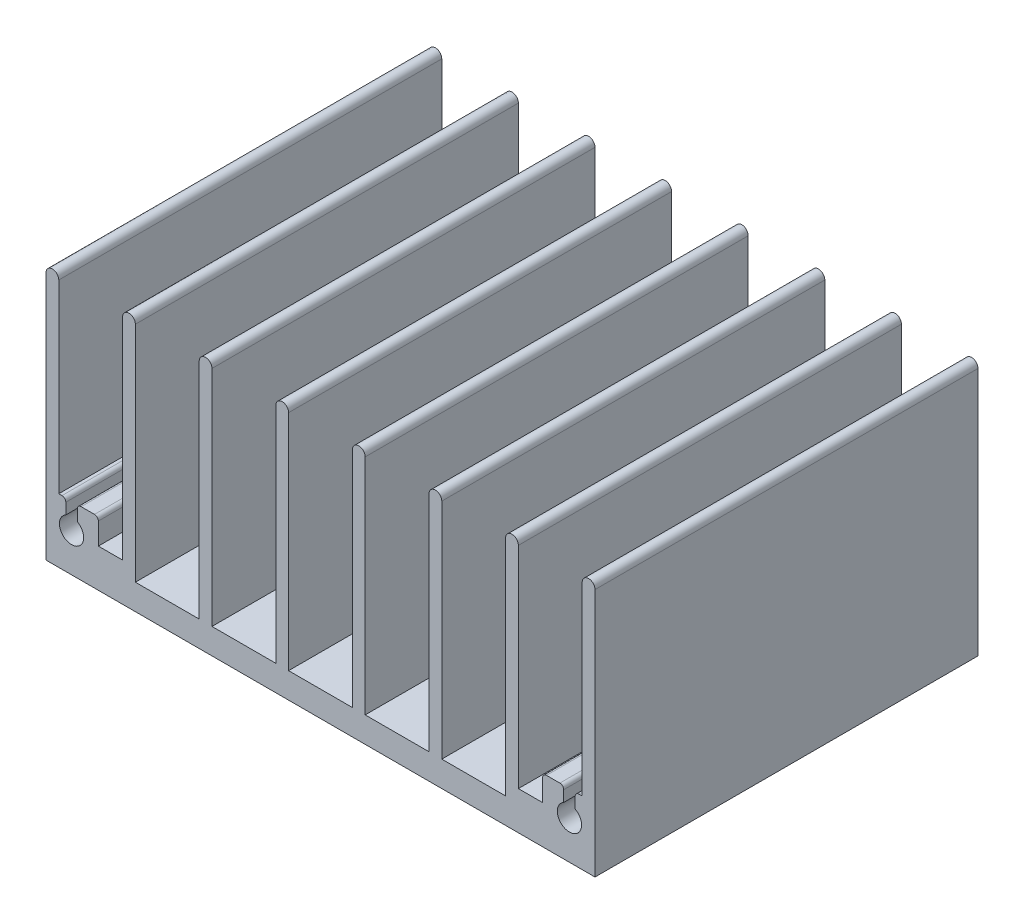
SolidWorks part; units mm, degrees
ref_plane "Front" through (0, 0, 0) normal (0, 0, 1) x (1, 0, 0)
ref_plane "Top" through (0, 0, 0) normal (0, 1, 0) x (1, 0, 0)
ref_plane "Right" through (0, 0, 0) normal (1, 0, 0) x (0, 0, -1)
sketch "Эскиз1" plane through (0, 0, 0) normal (0, 0, 1) x (1, 0, 0)
  line L10 (21.5, 0) -> (-21.5, 0)
  line L18 (21.5, 0) -> (21.5, 19.5)
  line L19 (20.5, 19.5) -> (20.5, 5)
  line L22 (24.9247, 20) -> (-25.9424, 20) construction
  line L23 (19.5, 3) -> (-19.5, 3) construction
  line L24 (0, 3) -> (0, 0) construction
  line L25 (19.05, 3.8367) -> (19.05, 5)
  line L26 (19.05, 5) -> (17.4, 5)
  line L27 (17.4, 5) -> (17.4, 3)
  line L28 (17.4, 3) -> (15.5, 3)
  line L29 (15.5, 3) -> (15.5, 19.5)
  line L30 (19.95, 3.8367) -> (19.95, 5)
  line L31 (19.95, 5) -> (20.5, 5)
  line L32 (14.5, 19.5) -> (14.5, 2)
  line L33 (14.5, 2) -> (9.5, 2)
  line L34 (9.5, 2) -> (9.5, 19.5)
  line L35 (8.5, 19.5) -> (8.5, 2)
  line L36 (8.5, 2) -> (3.5, 2)
  line L37 (3.5, 2) -> (3.5, 19.5)
  line L38 (2.5, 19.5) -> (2.5, 2)
  line L40 (-2.5, 2) -> (-2.5, 19.5)
  line L41 (-3.5, 19.5) -> (-3.5, 2)
  line L42 (-3.5, 2) -> (-8.5, 2)
  line L43 (-8.5, 2) -> (-8.5, 19.5)
  line L44 (-9.5, 19.5) -> (-9.5, 2)
  line L45 (-21.5, 0) -> (-21.5, 19.5)
  line L46 (-20.5, 19.5) -> (-20.5, 5)
  line L47 (-20.5, 5) -> (-19.95, 5)
  line L48 (-19.95, 5) -> (-19.95, 3.8367)
  line L49 (2.5, 2) -> (-2.5, 2)
  line L51 (-19.05, 3.8367) -> (-19.05, 5)
  line L52 (-19.05, 5) -> (-17.4, 5)
  line L53 (-17.4, 5) -> (-17.4, 3)
  line L54 (-17.4, 3) -> (-15.5, 3)
  line L55 (19.95, 5) -> (19.05, 5) construction
  line L56 (-19.95, 5) -> (-19.05, 5) construction
  line L57 (-15.5, 3) -> (-15.5, 19.5)
  line L58 (-14.5, 19.5) -> (-14.5, 2)
  line L59 (-14.5, 2) -> (-9.5, 2)
  line L60 (-20.5, 5) -> (-15.5, 5) construction
  line L61 (20.5, 5) -> (15.5, 5) construction
  arc A12 (21.5, 19.5) -> (20.5, 19.5) centre (21, 19.5) ccw
  arc A15 (19.05, 3.8367) -> (19.95, 3.8367) centre (19.5, 3) ccw
  arc A16 (-19.95, 3.8367) -> (-19.05, 3.8367) centre (-19.5, 3) ccw
  arc A17 (15.5, 19.5) -> (14.5, 19.5) centre (15, 19.5) ccw
  arc A18 (9.5, 19.5) -> (8.5, 19.5) centre (9, 19.5) ccw
  arc A19 (3.5, 19.5) -> (2.5, 19.5) centre (3, 19.5) ccw
  arc A20 (-2.5, 19.5) -> (-3.5, 19.5) centre (-3, 19.5) ccw
  arc A21 (-8.5, 19.5) -> (-9.5, 19.5) centre (-9, 19.5) ccw
  arc A22 (-21.5, 19.5) -> (-20.5, 19.5) centre (-21, 19.5) cw
  arc A23 (-15.5, 19.5) -> (-14.5, 19.5) centre (-15, 19.5) cw
  point P2 (0, 0)
  point P36 (-3.4686, 0.7542)
  point P37 (2.3591, 1.0573)
  point P53 (0, 2)
  point P64 (-2.4432, 1.1245)
  point P65 (0, 0)
  dimension "D1" = 43
  dimension "D6" = 0.95
  dimension "D10" = 5
  dimension "D11" = 2
  dimension "D2" = 1
  dimension "D4" = 39
  dimension "D9" = 1.9
  dimension "D3" = 20
  dimension "D5" = 3
  dimension "D7" = 5
  dimension "D8" = 0.9
extrude "Бобышка-Вытянуть1" add sketch "Эскиз1" along normal blind 30
fillet "Скругление1" radius 0.3 6 edges at (17.4, 5, 15) (19.05, 5, 15) (19.95, 5, 15) (-17.4, 5, 15) (-19.05, 5, 15) (-19.95, 5, 15)
